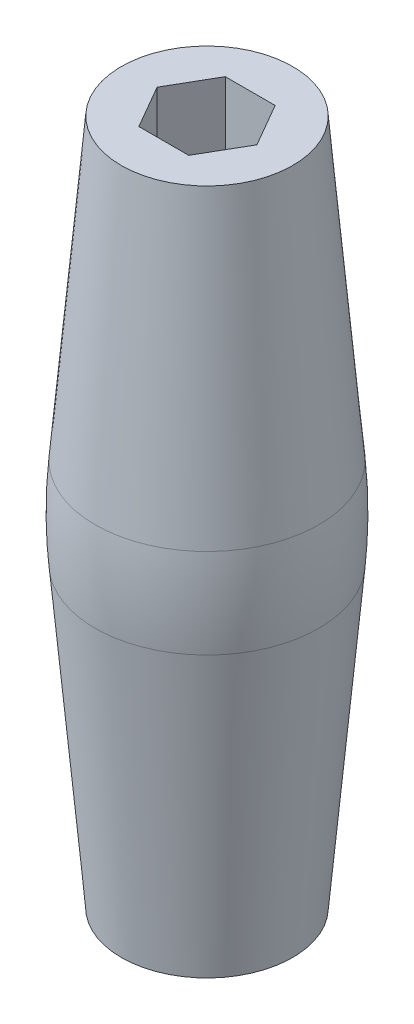
SolidWorks part; units mm, degrees
ref_plane "Front Plane" through (0, 0, 0) normal (0, 0, 1) x (1, 0, 0)
ref_plane "Top Plane" through (0, 0, 0) normal (0, 1, 0) x (1, 0, 0)
ref_plane "Right Plane" through (0, 0, 0) normal (1, 0, 0) x (0, 0, -1)
sketch "Sketch1" plane through (0, 0, 0) normal (0, 1, 0) x (1, 0, 0)
  circle A0 centre (0, 0) radius 12.7
  dimension "D1" = 25.4
extrude "Boss-Extrude1" add sketch "Sketch1" along normal blind 101.6
sketch "Sketch2" plane through (0, 101.6, 0) normal (0, 1, 0) x (1, 0, 0)
  circle A0 centre (0, 0) radius 12.7
extrude "Boss-Extrude2" add sketch "Sketch2" against normal blind 50.8 draft 5 draft outward yes
sketch "Sketch3" plane through (0, 0, 0) normal (0, -1, 0) x (-1, 0, 0)
  circle A0 centre (0, 0) radius 12.7
extrude "Boss-Extrude3" add sketch "Sketch3" against normal blind 50.8 draft 5 draft outward yes
sketch "Sketch5" plane through (0, 0, 0) normal (0, -1, 0) x (-1, 0, 0)
  line L1 (-7.391, 0) -> (-3.6955, -6.4008)
  line L2 (-3.6955, -6.4008) -> (3.6955, -6.4008)
  line L3 (3.6955, -6.4008) -> (7.391, 0)
  line L4 (7.391, 0) -> (3.6955, 6.4008)
  line L5 (3.6955, 6.4008) -> (-3.6955, 6.4008)
  line L6 (-3.6955, 6.4008) -> (-7.391, 0)
  circle A0 centre (0, 0) radius 6.4008 construction
  dimension "D1" = 12.8016
extrude "Cut-Extrude1" cut sketch "Sketch5" against normal through all
fillet "Fillet2" radius 76.2 1 edges at (0, 50.8, -17.1444)
